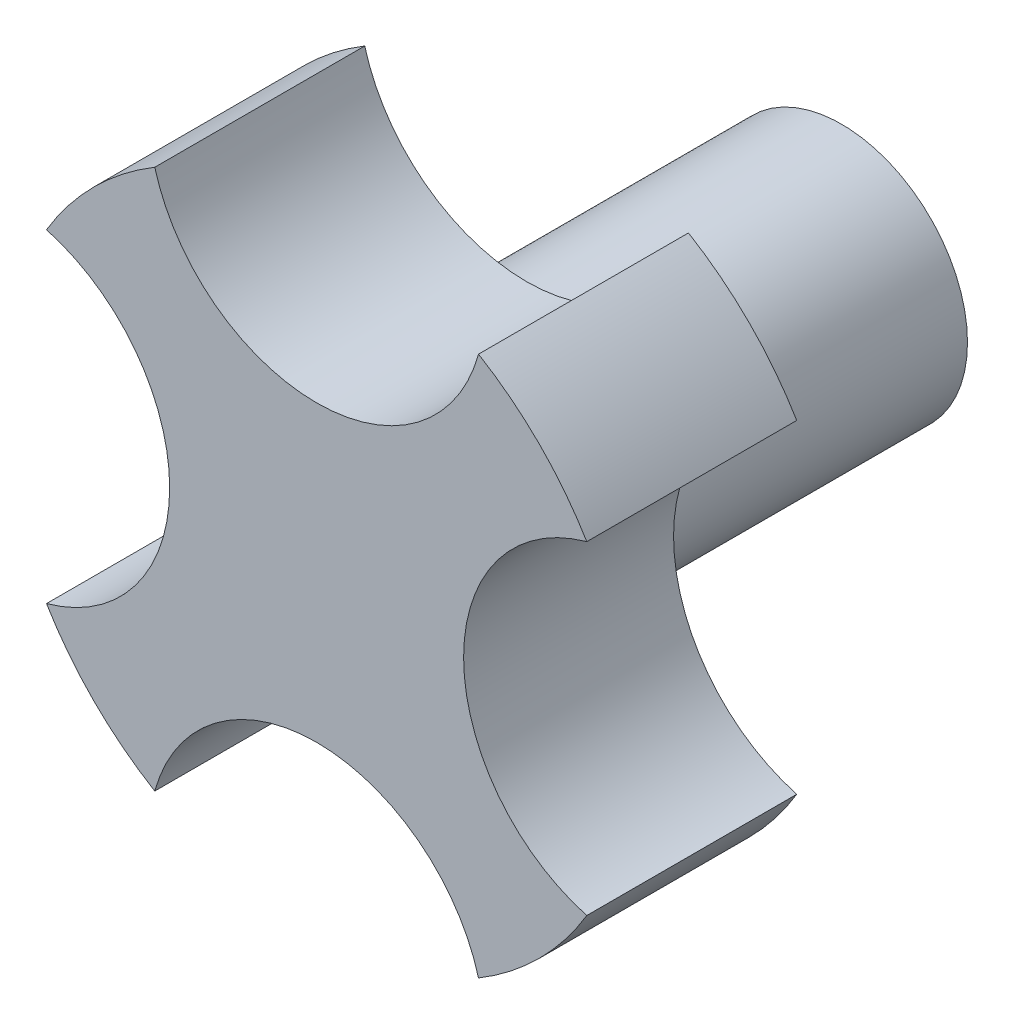
SolidWorks part; units mm, degrees
ref_plane "Ön Düzlem" through (0, 0, 0) normal (0, 0, 1) x (1, 0, 0)
ref_plane "Üst Düzlem" through (0, 0, 0) normal (0, 1, 0) x (1, 0, 0)
ref_plane "Sağ Düzlem" through (0, 0, 0) normal (1, 0, 0) x (0, 0, -1)
sketch "Çizim1" plane through (0, 0, 0) normal (0, 0, 1) x (1, 0, 0)
  circle A0 centre (0, 0) radius 4
  circle A1 centre (0, 0) radius 6
  dimension "D1" = 8
  dimension "D2" = 2
extrude "Yükseklik-Ekstrüzyon1" add sketch "Çizim1" along normal blind 15
sketch "Çizim2" plane through (0, 0, 15) normal (0, 0, 1) x (1, 0, 0)
  arc A1 (-7.7103, 12.8667) -> (-12.8667, 7.7103) centre (0, 0) ccw
  arc A2 (-7.7103, 12.8667) -> (7.7103, 12.8667) centre (0, 15) ccw
  arc A3 (12.8667, 7.7103) -> (12.8667, -7.7103) centre (15, 0) ccw
  arc A4 (7.7103, -12.8667) -> (-7.7103, -12.8667) centre (0, -15) ccw
  arc A5 (-12.8667, -7.7103) -> (-12.8667, 7.7103) centre (-15, 0) ccw
  arc A6 (12.8667, 7.7103) -> (7.7103, 12.8667) centre (0, 0) ccw
  arc A7 (7.7103, -12.8667) -> (12.8667, -7.7103) centre (0, 0) ccw
  arc A8 (-12.8667, -7.7103) -> (-7.7103, -12.8667) centre (0, 0) ccw
extrude "Yükseklik-Ekstrüzyon2" add sketch "Çizim2" along normal blind 10
sketch "Çizim3" plane through (0, 0, 0) normal (0, 1, 0) x (1, 0, 0)
  line L0 (0, 0) -> (0, -15)
  line L1 (7.7103, -15) -> (-7.7103, -15) construction
  circle A0 centre (0, -7.5) radius 1.5
  dimension "D1" = 3
extrude "Kes-Ekstrüzyon1" cut sketch "Çizim3" against normal blind 15 contours L0 A0 | L0 A0
pattern_circular "Dairesel Kaplama1" count 2 every 90 about axis through (0, 0, 15) along (0, 0, -1) of "Kes-Ekstrüzyon1"
